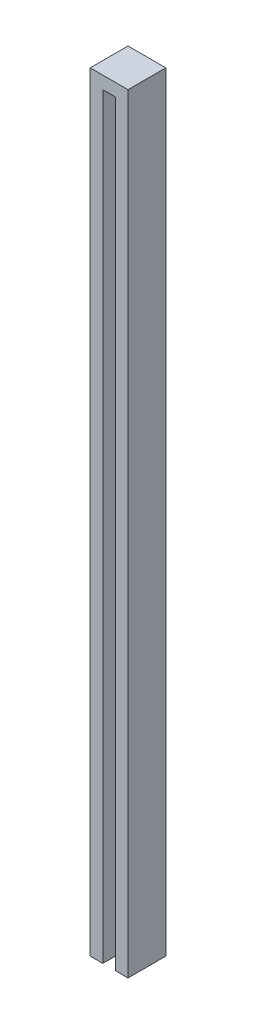
SolidWorks part; units mm, degrees
ref_plane "Front Plane" through (0, 0, 0) normal (0, 0, 1) x (1, 0, 0)
ref_plane "Top Plane" through (0, 0, 0) normal (0, 1, 0) x (1, 0, 0)
ref_plane "Right Plane" through (0, 0, 0) normal (1, 0, 0) x (0, 0, -1)
other "Center of Mass"
sketch "Sketch1" plane through (0, 0, 0) normal (0, 1, 0) x (1, 0, 0)
  line L0 (-75, -75) -> (75, -75)
  line L1 (-75, 75) -> (75, 75)
  line L2 (-75, 75) -> (-75, -75)
  line L4 (75, 75) -> (75, -75)
  line L5 (-75, 75) -> (75, -75) construction
  line L6 (-75, -75) -> (75, 75) construction
  point P0 (0, 0)
  point P6 (0, 48.2143)
  point P11 (0, -39.9351)
  dimension "D1" = 150
  dimension "D2" = 150
extrude "Boss-Extrude1" add sketch "Sketch1" along normal blind 3050
sketch "Sketch2" plane through (0, 0, 0) normal (0, -1, 0) x (1, 0, 0)
  line L0 (-75, 75) -> (75, 75) construction
  line L1 (-25, 75) -> (25, 75)
  line L2 (-25, 75) -> (-25, 25)
  line L3 (-25, 25) -> (25, 25)
  line L4 (25, 75) -> (25, 25)
  line L5 (75, -75) -> (-75, -75) construction
  line L6 (-25, -75) -> (25, -75)
  line L7 (-25, -75) -> (-25, -25)
  line L8 (-25, -25) -> (25, -25)
  line L9 (25, -75) -> (25, -25)
  line L10 (-75, -75) -> (-75, 75) construction
  line L11 (75, 75) -> (75, -75) construction
  dimension "D1" = 50
  dimension "D2" = 50
  dimension "D3" = 50
  dimension "D4" = 50
  dimension "D5" = 50
  dimension "D6" = 50
extrude "Cut-Extrude1" cut sketch "Sketch2" against normal blind 3000
sketch "Sketch3" plane through (0, 0, 0) normal (0, -1, 0) x (1, 0, 0)
  line L0 (-75, 75) -> (-25, 75) construction
  line L2 (-75, -75) -> (-75, 75) construction
  line L3 (0, -82.5) -> (0, 82.5) construction
  line L4 (82.5, 0) -> (-82.5, 0) construction
  circle A0 centre (-50, 50) radius 10
  circle A1 centre (50, 50) radius 10
  circle A2 centre (50, -50) radius 10
  circle A3 centre (-50, -50) radius 10
  point P6 (-75, 47.2899)
  dimension "D1" = 20
  dimension "D2" = 25
  dimension "D3" = 25
extrude "Cut-Extrude2" cut sketch "Sketch3" against normal blind 10
